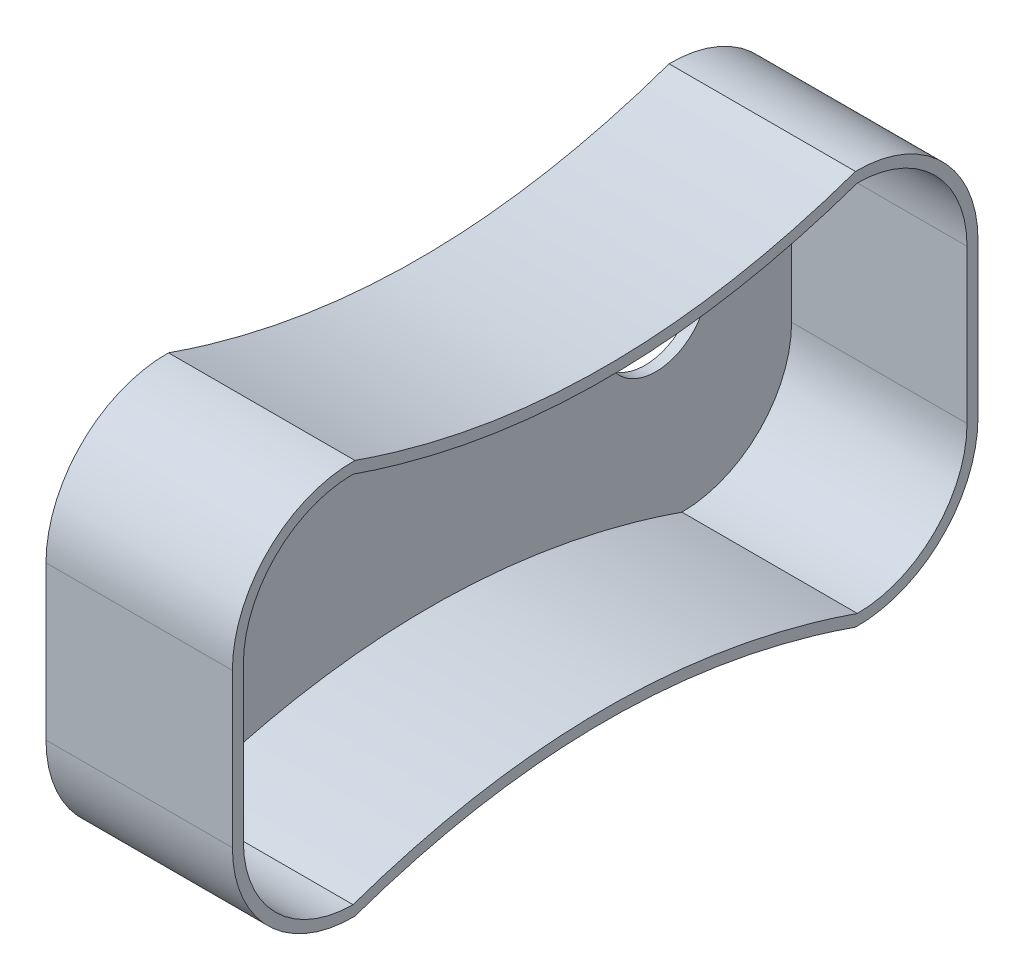
SolidWorks part; units mm, degrees
ref_plane "Alzado" through (0, 0, 0) normal (0, 0, 1) x (1, 0, 0)
ref_plane "Planta" through (0, 0, 0) normal (0, 1, 0) x (1, 0, 0)
ref_plane "Vista lateral" through (0, 0, 0) normal (1, 0, 0) x (0, 0, -1)
sketch "Croquis1" plane through (0, 0, 0) normal (1, 0, 0) x (0, 0, -1)
  line L2 (165, -35) -> (165, 35)
  line L4 (-165, -35) -> (-165, 35)
  line L5 (165, -85) -> (-165, 85) construction
  line L6 (165, 85) -> (-165, -85) construction
  arc A0 (-165, -35) -> (-115, -85) centre (-115, -35) ccw
  arc A1 (115, -85) -> (165, -35) centre (115, -35) ccw
  arc A2 (115, 85) -> (165, 35) centre (115, 35) cw
  arc A3 (-115, 85) -> (-165, 35) centre (-115, 35) ccw
  circle A5 centre (-100, 0) radius 23.6
  circle A6 centre (103.1, 0) radius 23.6
  spline S0 degree 2 poles (-115, 85) (0, 45) (115, 85) knots 0 0 0 1 1 1
  spline S1 degree 2 poles (-115, -85) (0, -45) (115, -85) knots 0 0 0 1 1 1
  point P0 (0, 0)
  dimension "D3" = 50
  dimension "D4" = 203.1
  dimension "D5" = 47.2
  dimension "D8" = 47.2
  dimension "D1" = 330
  dimension "D2" = 170
  dimension "D6" = 20
  dimension "D7" = 20
extrude "Saliente-Extruir1" add sketch "Croquis1" along normal blind 80
shell "Vaciado1" thickness 5
sketch "Croquis2" plane through (80, 0, 0) normal (1, 0, 0) x (0, 0, -1)
  circle A0 centre (-100, 0) radius 23.6
  circle A1 centre (103.1, 0) radius 23.6
extrude "Cortar-Extruir1" cut sketch "Croquis2" against normal blind 214
